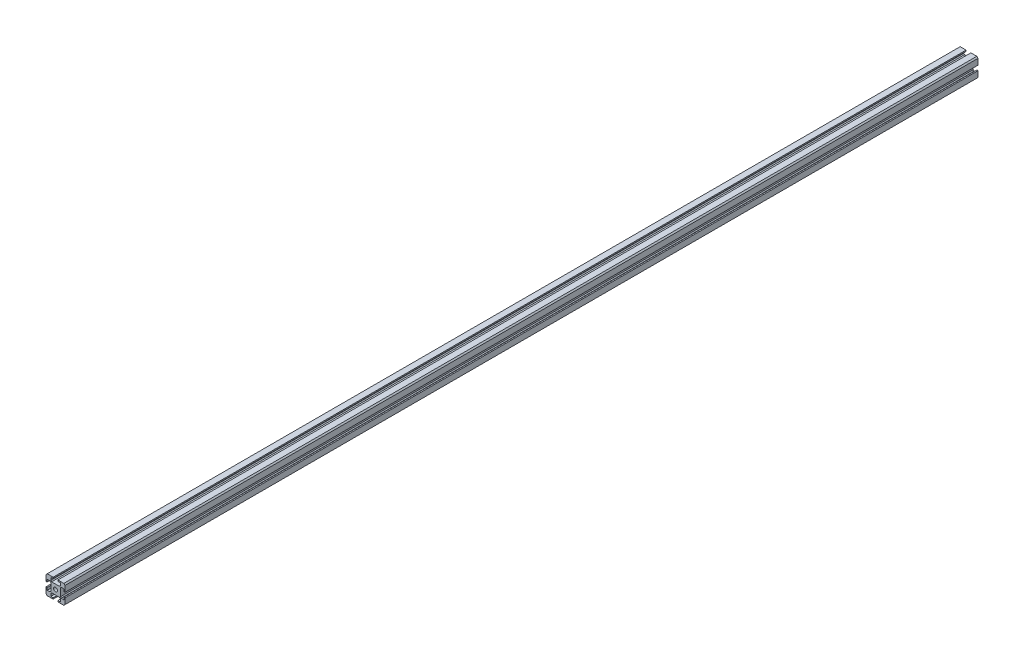
SolidWorks part; units mm, degrees
ref_plane "Front" through (0, 0, 0) normal (0, 0, 1) x (1, 0, 0)
ref_plane "Top" through (0, 0, 0) normal (0, 1, 0) x (1, 0, 0)
ref_plane "Right" through (0, 0, 0) normal (1, 0, 0) x (0, 0, -1)
sketch "Sketch1" plane through (0, 0, 0) normal (0, 0, 1) x (1, 0, 0)
  line L0 (-12.7, -12.7) -> (12.7, 12.7) construction
  line L1 (12.7, 3.175) -> (12.7, 12.7)
  line L2 (6.35, 5.2275) -> (6.35, -5.2275)
  line L3 (7.4725, 6.35) -> (6.35, 5.2275)
  line L4 (11.1125, 6.35) -> (7.4725, 6.35)
  line L5 (3.175, 12.7) -> (3.175, 11.1125)
  line L6 (3.175, 11.1125) -> (6.35, 11.1125)
  line L7 (6.35, 11.1125) -> (6.35, 7.4725)
  line L8 (6.35, 7.4725) -> (5.2275, 6.35)
  line L9 (5.2275, 6.35) -> (-5.2275, 6.35)
  line L10 (0, 0) -> (0, 15.8831) construction
  line L11 (3.175, 12.7) -> (12.7, 12.7)
  line L12 (11.1125, 3.175) -> (11.1125, 6.35)
  line L13 (12.7, 3.175) -> (11.1125, 3.175)
  line L14 (0, 0) -> (22.9897, 0) construction
  line L15 (12.7, -3.175) -> (11.1125, -3.175)
  line L16 (11.1125, -3.175) -> (11.1125, -6.35)
  line L17 (3.175, -12.7) -> (12.7, -12.7)
  line L18 (5.2275, -6.35) -> (-5.2275, -6.35)
  line L19 (6.35, -7.4725) -> (5.2275, -6.35)
  line L20 (6.35, -11.1125) -> (6.35, -7.4725)
  line L21 (3.175, -11.1125) -> (6.35, -11.1125)
  line L22 (3.175, -12.7) -> (3.175, -11.1125)
  line L23 (11.1125, -6.35) -> (7.4725, -6.35)
  line L24 (7.4725, -6.35) -> (6.35, -5.2275)
  line L25 (12.7, -3.175) -> (12.7, -12.7)
  line L26 (-12.7, -3.175) -> (-12.7, -12.7)
  line L27 (-7.4725, -6.35) -> (-6.35, -5.2275)
  line L28 (-11.1125, -6.35) -> (-7.4725, -6.35)
  line L29 (-3.175, -12.7) -> (-3.175, -11.1125)
  line L30 (-3.175, -11.1125) -> (-6.35, -11.1125)
  line L31 (-6.35, -11.1125) -> (-6.35, -7.4725)
  line L32 (-6.35, -7.4725) -> (-5.2275, -6.35)
  line L33 (-3.175, -12.7) -> (-12.7, -12.7)
  line L34 (-11.1125, -3.175) -> (-11.1125, -6.35)
  line L35 (-12.7, -3.175) -> (-11.1125, -3.175)
  line L36 (-12.7, 3.175) -> (-11.1125, 3.175)
  line L37 (-11.1125, 3.175) -> (-11.1125, 6.35)
  line L38 (-3.175, 12.7) -> (-12.7, 12.7)
  line L39 (-6.35, 7.4725) -> (-5.2275, 6.35)
  line L40 (-6.35, 11.1125) -> (-6.35, 7.4725)
  line L41 (-3.175, 11.1125) -> (-6.35, 11.1125)
  line L42 (-3.175, 12.7) -> (-3.175, 11.1125)
  line L43 (-11.1125, 6.35) -> (-7.4725, 6.35)
  line L44 (-7.4725, 6.35) -> (-6.35, 5.2275)
  line L45 (-6.35, 5.2275) -> (-6.35, -5.2275)
  line L46 (-12.7, 3.175) -> (-12.7, 12.7)
  circle A0 centre (0, 0) radius 2.6035
  point P9 (-6.35, 0)
  point P31 (6.35, 0)
  point P41 (0, -6.35)
  point P48 (0, 6.35)
  dimension "D1" = 5.207
  dimension "D2" = 25.4
  dimension "D4" = 6.35
  dimension "D5" = 3.175
  dimension "D6" = 6.35
  dimension "D7" = 1.5875
  dimension "D8" = 1.5875
extrude "Extrude1" add sketch "Sketch1" along normal blind 1219.2
chamfer "Chamfer1" distance 1.5875 angle 45 4 edges at (-12.7, -12.7, 609.6) (12.7, -12.7, 609.6) (12.7, 12.7, 609.6) (-12.7, 12.7, 609.6)
